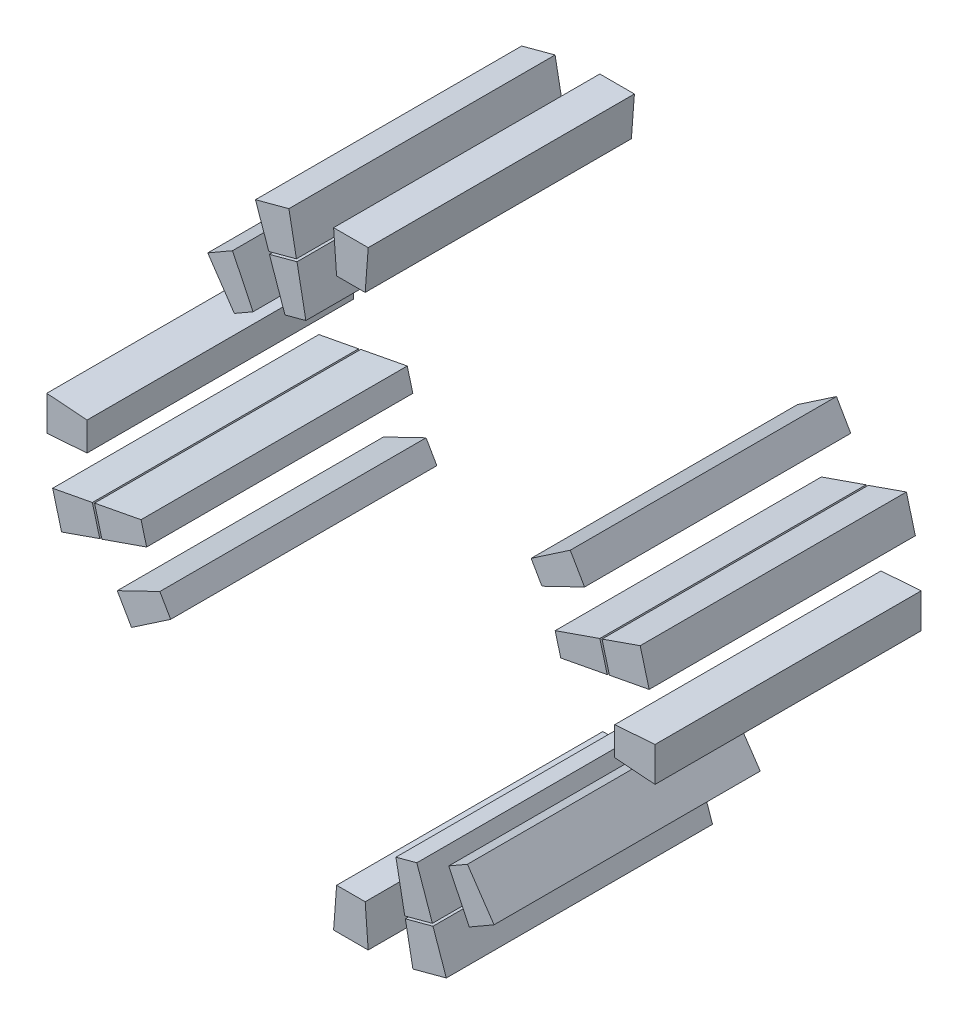
SolidWorks part; units mm, degrees
ref_plane "Спереди" through (0, 0, 0) normal (0, 0, 1) x (1, 0, 0)
ref_plane "Сверху" through (0, 0, 0) normal (0, 1, 0) x (1, 0, 0)
ref_plane "Справа" through (0, 0, 0) normal (1, 0, 0) x (0, 0, -1)
sketch "Эскиз1" plane through (0, 0, 0) normal (0, 0, 1) x (1, 0, 0)
  line L0 (39.6419, -2.1473) -> (45.7, -2.6)
  line L1 (45.7, -2.6) -> (45.7, 2.6)
  line L2 (45.7, 2.6) -> (39.6419, 2.1473)
  line L3 (39.6419, 2.1473) -> (39.6419, -2.1473)
  line L4 (31.5321, 6.7667) -> (38.5167, 8.0974)
  line L5 (38.5167, 8.0974) -> (37.4051, 12.2457)
  line L6 (37.4051, 12.2457) -> (30.691, 9.9059)
  line L7 (30.691, 9.9059) -> (31.5321, 6.7667)
  line L8 (38.8469, 8.1859) -> (44.8157, 9.3166)
  line L9 (44.8157, 9.3166) -> (43.4699, 14.3394)
  line L10 (43.4699, 14.3394) -> (37.7354, 12.3342)
  line L11 (37.7354, 12.3342) -> (38.8469, 8.1859)
  line L12 (28.7063, 14.6972) -> (35.1085, 17.7904)
  line L13 (35.1085, 17.7904) -> (32.9611, 21.5096)
  line L14 (32.9611, 21.5096) -> (27.0813, 17.5118)
  line L15 (27.0813, 17.5118) -> (28.7063, 14.6972)
  line L16 (2.1473, 39.6419) -> (2.6, 45.7)
  line L17 (2.6, 45.7) -> (-2.6, 45.7)
  line L18 (-2.6, 45.7) -> (-2.1473, 39.6419)
  line L19 (-2.1473, 39.6419) -> (2.1473, 39.6419)
  line L20 (-6.7667, 31.5321) -> (-8.0974, 38.5167)
  line L21 (-8.0974, 38.5167) -> (-12.2457, 37.4051)
  line L22 (-12.2457, 37.4051) -> (-9.9059, 30.691)
  line L23 (-9.9059, 30.691) -> (-6.7667, 31.5321)
  line L24 (-8.1859, 38.8469) -> (-9.3166, 44.8157)
  line L25 (-9.3166, 44.8157) -> (-14.3394, 43.4699)
  line L26 (-14.3394, 43.4699) -> (-12.3342, 37.7354)
  line L27 (-12.3342, 37.7354) -> (-8.1859, 38.8469)
  line L28 (-14.6972, 28.7063) -> (-17.7904, 35.1085)
  line L29 (-17.7904, 35.1085) -> (-21.5096, 32.9611)
  line L30 (-21.5096, 32.9611) -> (-17.5118, 27.0813)
  line L31 (-17.5118, 27.0813) -> (-14.6972, 28.7063)
  line L32 (-39.6419, 2.1473) -> (-45.7, 2.6)
  line L33 (-45.7, 2.6) -> (-45.7, -2.6)
  line L34 (-45.7, -2.6) -> (-39.6419, -2.1473)
  line L35 (-39.6419, -2.1473) -> (-39.6419, 2.1473)
  line L36 (-31.5321, -6.7667) -> (-38.5167, -8.0974)
  line L37 (-38.5167, -8.0974) -> (-37.4051, -12.2457)
  line L38 (-37.4051, -12.2457) -> (-30.691, -9.9059)
  line L39 (-30.691, -9.9059) -> (-31.5321, -6.7667)
  line L40 (-38.8469, -8.1859) -> (-44.8157, -9.3166)
  line L41 (-44.8157, -9.3166) -> (-43.4699, -14.3394)
  line L42 (-43.4699, -14.3394) -> (-37.7354, -12.3342)
  line L43 (-37.7354, -12.3342) -> (-38.8469, -8.1859)
  line L44 (-28.7063, -14.6972) -> (-35.1085, -17.7904)
  line L45 (-35.1085, -17.7904) -> (-32.9611, -21.5096)
  line L46 (-32.9611, -21.5096) -> (-27.0813, -17.5118)
  line L47 (-27.0813, -17.5118) -> (-28.7063, -14.6972)
  line L48 (-2.1473, -39.6419) -> (-2.6, -45.7)
  line L49 (-2.6, -45.7) -> (2.6, -45.7)
  line L50 (2.6, -45.7) -> (2.1473, -39.6419)
  line L51 (2.1473, -39.6419) -> (-2.1473, -39.6419)
  line L52 (6.7667, -31.5321) -> (8.0974, -38.5167)
  line L53 (8.0974, -38.5167) -> (12.2457, -37.4051)
  line L54 (12.2457, -37.4051) -> (9.9059, -30.691)
  line L55 (9.9059, -30.691) -> (6.7667, -31.5321)
  line L56 (8.1859, -38.8469) -> (9.3166, -44.8157)
  line L57 (9.3166, -44.8157) -> (14.3394, -43.4699)
  line L58 (14.3394, -43.4699) -> (12.3342, -37.7354)
  line L59 (12.3342, -37.7354) -> (8.1859, -38.8469)
  line L60 (14.6972, -28.7063) -> (17.7904, -35.1085)
  line L61 (17.7904, -35.1085) -> (21.5096, -32.9611)
  line L62 (21.5096, -32.9611) -> (17.5118, -27.0813)
  line L63 (17.5118, -27.0813) -> (14.6972, -28.7063)
extrude "Coil_sides" add sketch "Эскиз1" along normal blind 40 from offset 20 separate body
